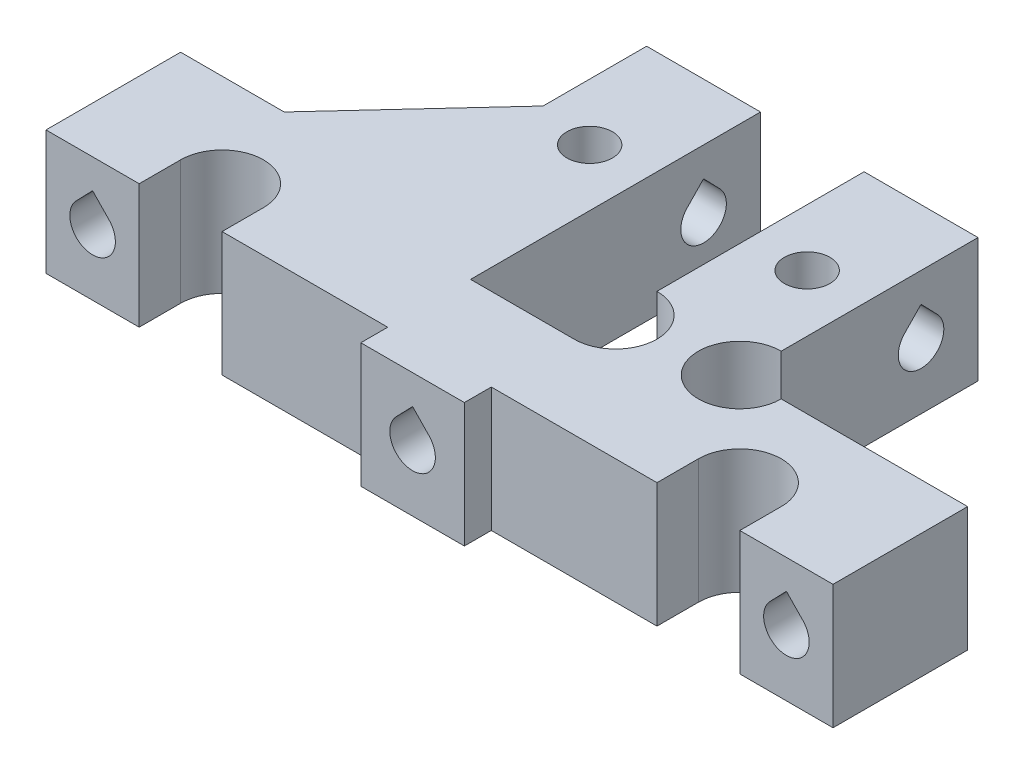
SolidWorks part; units mm, degrees
ref_plane "Front Plane" through (0, 0, 0) normal (0, 0, 1) x (1, 0, 0)
ref_plane "Top Plane" through (0, 0, 0) normal (0, 1, 0) x (1, 0, 0)
ref_plane "Right Plane" through (0, 0, 0) normal (1, 0, 0) x (0, 0, -1)
ref_plane "Plane1" through (0, 23, 0) normal (0, 1, 0) x (-1, 0, 0)
sketch "Sketch1" plane through (0, 23, 0) normal (0, 1, 0) x (-1, 0, 0)
  line L0 (-38, -36) -> (38, -36)
  line L1 (38, -36) -> (38, 0)
  line L2 (38, 0) -> (29, 0)
  line L3 (29, 0) -> (29, -4)
  line L4 (21, -4) -> (21, 2.6)
  line L5 (21, 2.6) -> (-38, 2.6)
  line L6 (-38, 2.6) -> (-38, -36)
  arc A0 (29, -4) -> (21, -4) centre (25, -4) cw
extrude "Boss-Extrude1" add sketch "Sketch1" against normal blind 12
sketch "Sketch2" plane through (0, 11, 0) normal (0, -1, 0) x (1, 0, 0)
  line L0 (-5, -36) -> (5, -36)
  line L1 (5, -36) -> (5, -16)
  line L2 (5, -8) -> (-5, -8)
  line L3 (-5, -8) -> (-5, -36)
  arc A0 (5, -16) -> (5, -8) centre (5, -12) ccw
extrude "Cut-Extrude1" cut sketch "Sketch2" against normal through all
sketch "Sketch3" plane through (0, 11, 0) normal (0, -1, 0) x (1, 0, 0)
  line L0 (-38, -36) -> (-16, -36)
  line L1 (-16, -36) -> (-16, -26)
  line L2 (-16, -26) -> (-28, -13)
  line L3 (-28, -13) -> (-38, -13)
  line L4 (-38, -13) -> (-38, -36)
extrude "Cut-Extrude2" cut sketch "Sketch3" against normal through all
sketch "Sketch4" plane through (0, 11, 0) normal (0, -1, 0) x (1, 0, 0)
  line L0 (-21, 2.6) -> (-21, 0)
  line L1 (-21, 0) -> (-5, 0)
  line L2 (-5, 0) -> (-5, 2.6)
  line L3 (-5, 2.6) -> (-21, 2.6)
extrude "Cut-Extrude3" cut sketch "Sketch4" against normal through all
sketch "Sketch5" plane through (0, 11, 0) normal (0, -1, 0) x (1, 0, 0)
  line L0 (38, 2.6) -> (5, 2.6)
  line L1 (5, 2.6) -> (5, 0)
  line L2 (5, 0) -> (38, 0)
  line L3 (38, 0) -> (38, 2.6)
extrude "Cut-Extrude4" cut sketch "Sketch5" against normal through all
sketch "Sketch6" plane through (0, 11, 0) normal (0, -1, 0) x (1, 0, 0)
  line L0 (29, 0) -> (21, 0)
  line L1 (21, 0) -> (21, -4)
  line L2 (29, -4) -> (29, 0)
  arc A0 (21, -4) -> (29, -4) centre (25, -4) ccw
extrude "Cut-Extrude5" cut sketch "Sketch6" against normal through all
sketch "Sketch7" plane through (0, 11, 0) normal (0, -1, 0) x (1, 0, 0)
  line L0 (38, -13) -> (16, -13)
  line L1 (16, -13) -> (16, -36)
  line L2 (16, -36) -> (38, -36)
  line L3 (38, -36) -> (38, -13)
extrude "Cut-Extrude6" cut sketch "Sketch7" against normal through all
sketch "Sketch8" plane through (0, 0, -13) normal (0, 0, -1) x (-1, 0, 0)
  line L0 (35.0825, 18.5282) -> (33.5, 20.167)
  line L1 (33.5, 20.167) -> (31.9175, 18.5282)
  arc A0 (31.9175, 18.5282) -> (35.0825, 18.5282) centre (33.5, 17) ccw
extrude "Cut-Extrude7" cut sketch "Sketch8" against normal through all
sketch "Sketch9" plane through (16, 0, 0) normal (1, 0, 0) x (0, 0, -1)
  line L0 (32.0825, 18.5282) -> (30.5, 20.167)
  line L1 (30.5, 20.167) -> (28.9175, 18.5282)
  arc A0 (28.9175, 18.5282) -> (32.0825, 18.5282) centre (30.5, 17) ccw
extrude "Cut-Extrude8" cut sketch "Sketch9" against normal up to next
sketch "Sketch10" plane through (0, 0, 0) normal (0, 0, 1) x (1, 0, 0)
  line L0 (35.0825, 18.5282) -> (33.5, 20.167)
  line L1 (33.5, 20.167) -> (31.9175, 18.5282)
  arc A0 (31.9175, 18.5282) -> (35.0825, 18.5282) centre (33.5, 17) ccw
extrude "Cut-Extrude9" cut sketch "Sketch10" against normal through all
sketch "Sketch11" plane through (-5, 0, 0) normal (1, 0, 0) x (0, 0, -1)
  line L0 (32.0825, 18.5282) -> (30.5, 20.167)
  line L1 (30.5, 20.167) -> (28.9175, 18.5282)
  arc A0 (28.9175, 18.5282) -> (32.0825, 18.5282) centre (30.5, 17) ccw
extrude "Cut-Extrude10" cut sketch "Sketch11" against normal through all
sketch "Sketch12" plane through (0, 0, -8) normal (0, 0, -1) x (-1, 0, 0)
  line L0 (1.5825, 18.5282) -> (0, 20.167)
  line L1 (0, 20.167) -> (-1.5825, 18.5282)
  arc A0 (-1.5825, 18.5282) -> (1.5825, 18.5282) centre (0, 17) ccw
extrude "Cut-Extrude11" cut sketch "Sketch12" against normal through all
hole_wizard "Hole1" positions "Sketch14" profile "Sketch13" legacy
sketch "Sketch14" plane through (0, 11, 0) normal (0, -1, 0) x (1, 0, 0)
  point P0 (16, -13)
sketch "Sketch13" plane through (16, 11, -13) normal (1, 0, 0) x (0, 0, -1)
  line L0 (0, 0) -> (0, 12)
  line L1 (0, 12) -> (4, 12)
  line L2 (4, 12) -> (4, 0)
  line L3 (4, 0) -> (0, 0)
  line L4 (0, 110) -> (0, -10) construction
  dimension "Diameter" = 8
  dimension "Depth" = 12
hole_wizard "Hole2" positions "Sketch16" profile "Sketch15" legacy
sketch "Sketch16" plane through (0, 11, 0) normal (0, -1, 0) x (1, 0, 0)
  point P0 (-10.5, -25)
sketch "Sketch15" plane through (-10.5, 11, -25) normal (1, 0, 0) x (0, 0, -1)
  line L0 (0, 0) -> (0, 12)
  line L1 (0, 12) -> (2.2, 12)
  line L2 (2.2, 12) -> (2.2, 0)
  line L3 (2.2, 0) -> (0, 0)
  line L4 (0, 110) -> (0, -10) construction
  dimension "Diameter" = 4.4
  dimension "Depth" = 12
hole_wizard "Hole3" positions "Sketch18" profile "Sketch17" legacy
sketch "Sketch18" plane through (0, 11, 0) normal (0, -1, 0) x (1, 0, 0)
  point P0 (10.5, -25)
sketch "Sketch17" plane through (10.5, 11, -25) normal (1, 0, 0) x (0, 0, -1)
  line L0 (0, 0) -> (0, 12)
  line L1 (0, 12) -> (2.2, 12)
  line L2 (2.2, 12) -> (2.2, 0)
  line L3 (2.2, 0) -> (0, 0)
  line L4 (0, 110) -> (0, -10) construction
  dimension "Diameter" = 4.4
  dimension "Depth" = 12
